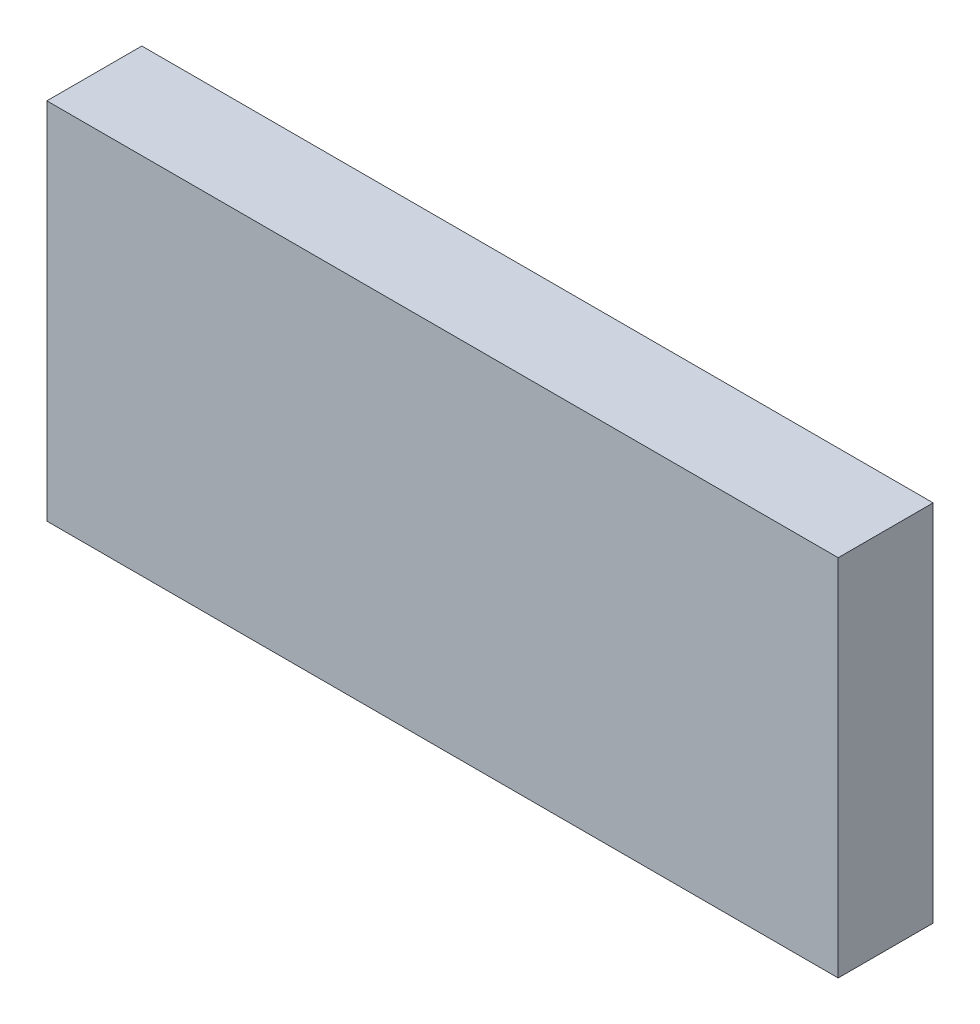
SolidWorks part; units mm, degrees
ref_plane "Plan de face" through (0, 0, 0) normal (0, 0, 1) x (1, 0, 0)
ref_plane "Plan de dessus" through (0, 0, 0) normal (0, 1, 0) x (1, 0, 0)
ref_plane "Plan de droite" through (0, 0, 0) normal (1, 0, 0) x (0, 0, -1)
sketch "Esquisse1" plane through (0, 0, 0) normal (0, 0, 1) x (1, 0, 0)
  line L1 (0, 0) -> (-50, 0)
  line L2 (0, 0) -> (0, 23)
  line L3 (0, 23) -> (-50, 23)
  line L4 (-50, 0) -> (-50, 23)
  dimension "D1" = 23
  dimension "D2" = 50
extrude "Boss.-Extru.1" add sketch "Esquisse1" along normal blind 6
